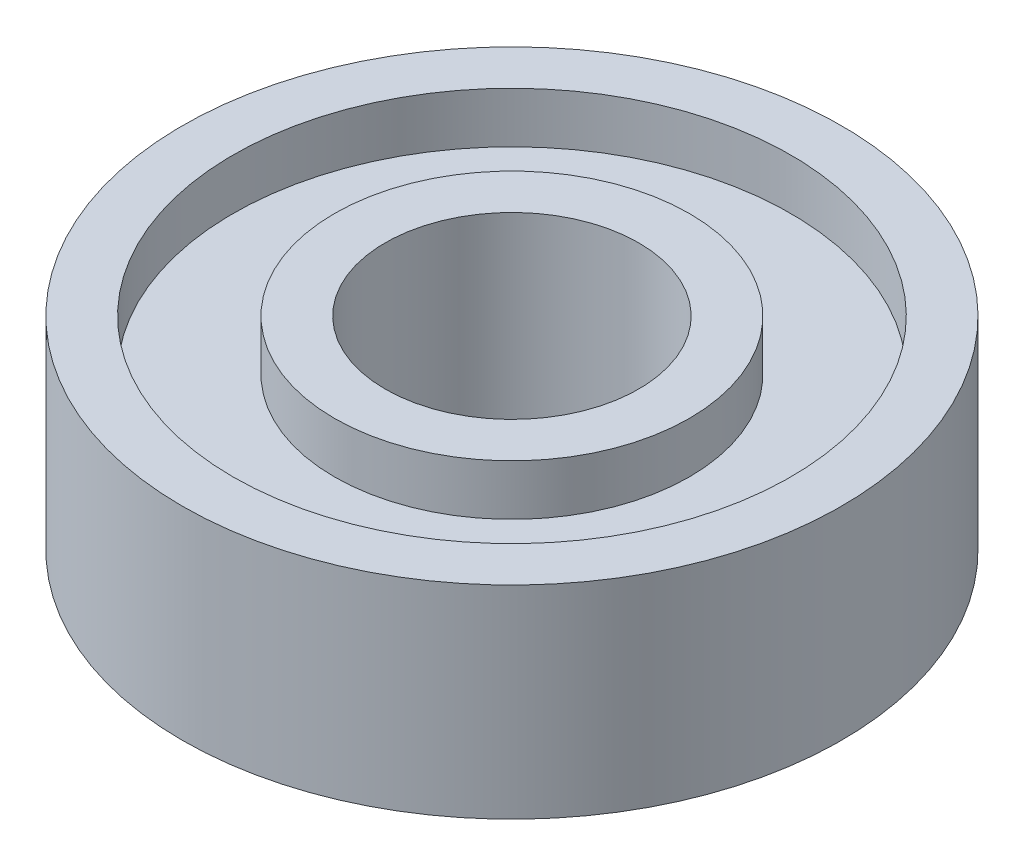
SolidWorks part; units mm, degrees
ref_plane "Front Plane" through (0, 0, 0) normal (0, 0, 1) x (1, 0, 0)
ref_plane "Top Plane" through (0, 0, 0) normal (0, 1, 0) x (1, 0, 0)
ref_plane "Right Plane" through (0, 0, 0) normal (1, 0, 0) x (0, 0, -1)
sketch "Sketch1" plane through (0, 0, 0) normal (0, 1, 0) x (1, 0, 0)
  circle A0 centre (0, 0) radius 6.5
  circle A1 centre (0, 0) radius 2.5
  dimension "D1" = 13
  dimension "D2" = 5
extrude "Boss-Extrude1" add sketch "Sketch1" along normal blind 4
sketch "Sketch2" plane through (0, 4, 0) normal (0, 1, 0) x (1, 0, 0)
  circle A0 centre (0, 0) radius 3.5
  circle A1 centre (0, 0) radius 5.5
  dimension "D1" = 11
  dimension "D2" = 7
extrude "Cut-Extrude1" cut sketch "Sketch2" against normal blind 1
sketch "Sketch3" plane through (0, 0, 0) normal (0, -1, 0) x (1, 0, 0)
  circle A0 centre (0, 0) radius 3.5
  circle A1 centre (0, 0) radius 5.5
  dimension "D1" = 11
  dimension "D2" = 7
extrude "Cut-Extrude2" cut sketch "Sketch3" against normal blind 1
